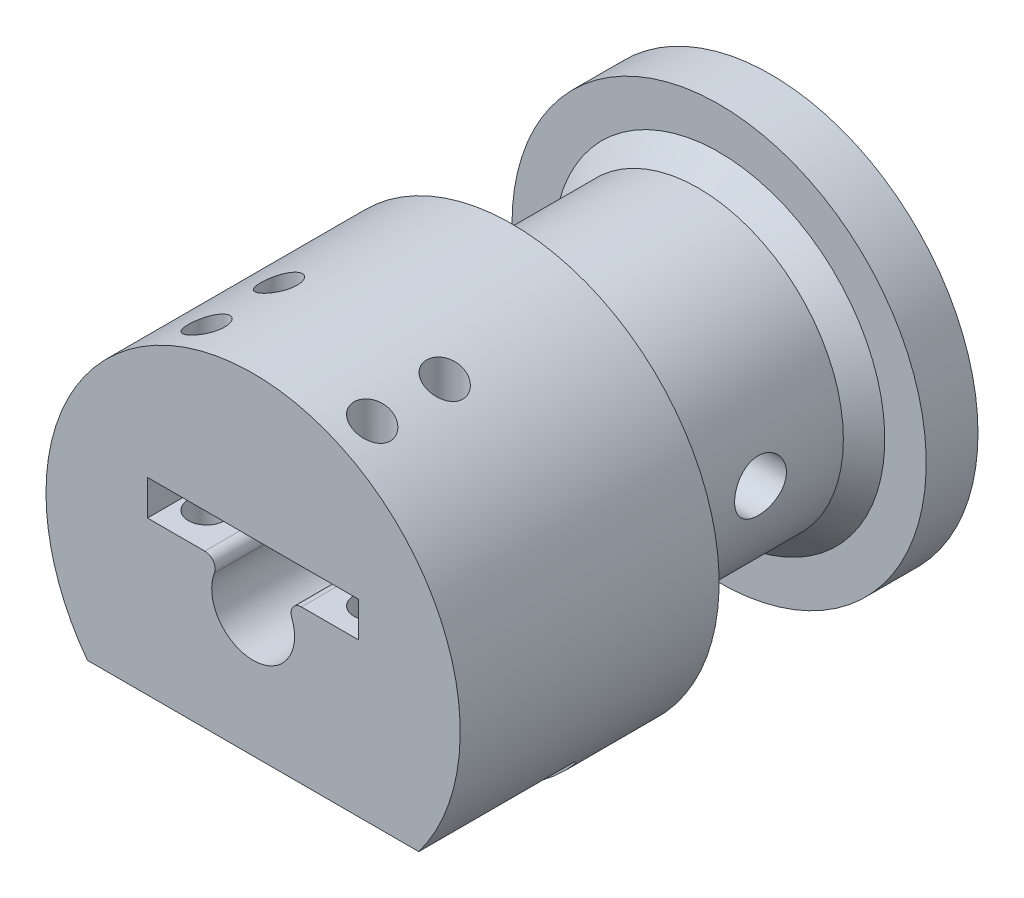
SolidWorks part; units mm, degrees
material "ABS"
ref_plane "Płaszczyzna przednia" through (0, 0, 0) normal (0, 0, 1) x (1, 0, 0)
ref_plane "Płaszczyzna górna" through (0, 0, 0) normal (0, 1, 0) x (1, 0, 0)
ref_plane "Płaszczyzna prawa" through (0, 0, 0) normal (1, 0, 0) x (0, 0, -1)
sketch "Szkic1" plane through (0, 0, 0) normal (0, 0, 1) x (1, 0, 0)
  circle A0 centre (0, 0) radius 4
  circle A1 centre (0, 0) radius 20
  dimension "D1" = 8
  dimension "D2" = 40
extrude "Dodanie-wyciągnięcie1" add sketch "Szkic1" along normal blind 50
sketch "Szkic2" plane through (0, 0, 50) normal (0, 0, 1) x (1, 0, 0)
  line L0 (4.6648, 2.8) -> (10.2, 2.8)
  line L1 (-10.2, 2.8) -> (-4.6648, 2.8)
  line L2 (-10.2, 2.8) -> (-10.2, 6.2)
  line L3 (-10.2, 6.2) -> (10.2, 6.2)
  line L4 (10.2, 2.8) -> (10.2, 6.2)
  circle A0 centre (0, 0) radius 4 construction
  arc A1 (-3.7318, 1.44) -> (3.7318, 1.44) centre (0, 0) ccw
  arc A2 (4.6648, 2.8) -> (3.7318, 1.44) centre (4.6648, 1.8) ccw
  arc A3 (-4.6648, 2.8) -> (-3.7318, 1.44) centre (-4.6648, 1.8) cw
  point P10 (2.8566, 2.8)
  point P13 (0, 6.2)
  circle M7 centre (0, 0) radius 4
  dimension "D4" = 1
  dimension "D1" = 3.4
  dimension "D2" = 2.8
  dimension "D3" = 20.4
extrude "Wytnij-wyciągnięcie1" cut sketch "Szkic2" against normal blind 14.5 contours L1 L4 L3 L2 M7
sketch "Szkic3" plane through (0, 2.8, 0) normal (0, 1, 0) x (1, 0, 0)
  line L0 (0, -51.4536) -> (0, -28.712) construction
  line L1 (-10.2, -50) -> (-4.6648, -50) construction
  line L2 (-10.2, -35.5) -> (-4.6648, -35.5) construction
  circle A0 centre (-8, -46.5) radius 1.75
  circle A1 centre (-8, -39.5) radius 1.75
  circle A2 centre (8, -46.5) radius 1.75
  circle A3 centre (8, -39.5) radius 1.75
  dimension "D1" = 3.5
  dimension "D2" = 8
  dimension "D3" = 3.5
  dimension "D4" = 4
extrude "Wytnij-wyciągnięcie2" cut sketch "Szkic3" against normal through all and the other way through all
ref_plane "Płaszczyzna1" through (20, 0, 0) normal (1, 0, 0) x (0, 0, -1)
sketch "Szkic4" plane through (20, 0, 0) normal (1, 0, 0) x (0, 0, -1)
  line L5 (-50, -20) -> (-34, -20)
  line L6 (-50, -20) -> (-50, -12)
  line L7 (-50, -12) -> (-34, -12)
  line L8 (-34, -20) -> (-34, -12)
  dimension "D1" = 16
  dimension "D2" = 8
extrude "Wytnij-wyciągnięcie3" cut sketch "Szkic4" against normal through all
sketch "Szkic6" plane through (0, 0, 0) normal (1, 0, 0) x (0, 0, -1)
  line L0 (0, 20) -> (-50, 20) construction
  line L1 (-25, 20) -> (-5, 20)
  line L2 (-25, 20) -> (-25, 14)
  line L3 (-25, 14) -> (-5, 14)
  line L4 (-5, 20) -> (-5, 14)
  line L5 (0, -20) -> (0, 20) construction
  line L6 (0, 0) -> (-55.9301, 0) construction
  dimension "D1" = 20
  dimension "D2" = 5
  dimension "D3" = 6
revolve "Wycięcie-obrót1" cut sketch "Szkic6" angle 360 about L6
chamfer "Sfazowanie1" distance 2 angle 45 2 edges at (-14, 0, 5) (-14, 0, 25)
sketch "Szkic7" plane through (0, 0, 0) normal (1, 0, 0) x (0, 0, -1)
  line L0 (-5, 16) -> (-5, -16) construction
  circle A0 centre (-15, 0) radius 2.5
  dimension "D2" = 5
  dimension "D1" = 10
extrude "Wytnij-wyciągnięcie4" cut sketch "Szkic7" against normal through all and the other way through all
chamfer "Sfazowanie2" distance 1 angle 45 1 edges at (0, -12, 34)
